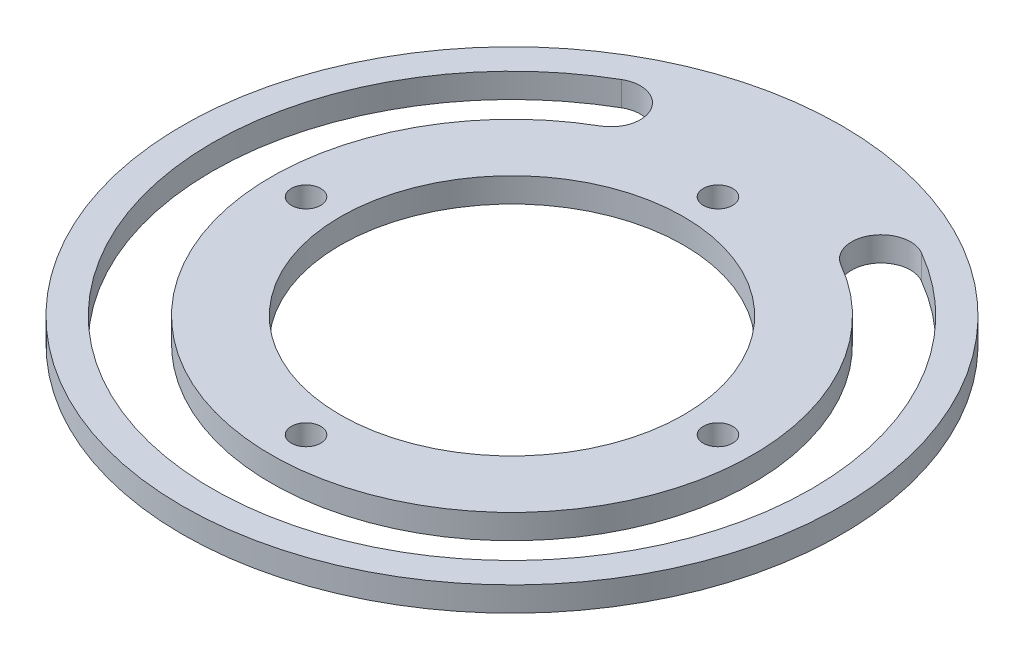
SolidWorks part; units mm, degrees
ref_plane "Front Plane" through (0, 0, 0) normal (0, 0, 1) x (1, 0, 0)
ref_plane "Top Plane" through (0, 0, 0) normal (0, 1, 0) x (1, 0, 0)
ref_plane "Right Plane" through (0, 0, 0) normal (1, 0, 0) x (0, 0, -1)
sketch "Sketch1" plane through (0, 0, 0) normal (0, 1, 0) x (1, 0, 0)
  line L0 (0, 0) -> (0, 26.67) construction
  circle A0 centre (0, 0) radius 22.225
  circle A1 centre (0, 0) radius 42.672
  circle A2 centre (0, 26.67) radius 1.905
  circle A7 centre (26.67, 0) radius 1.905
  circle A8 centre (0, -26.67) radius 1.905
  circle A9 centre (-26.67, 0) radius 1.905
  point P16 (0.3175, -0.3175)
  point P17 (0, 0)
  dimension "D1" = 44.45
  dimension "D3" = 3.81
  dimension "D2" = 85.344
  dimension "D4" = 26.67
  dimension "D5" = 4
extrude "Boss-Extrude1" add sketch "Sketch1" along normal blind 3.175
sketch "Sketch2" plane through (0, 3.175, 0) normal (0, 1, 0) x (1, 0, 0)
  line L0 (0, 0) -> (31.1785, 0) construction
  line L1 (0, 0) -> (0, 26.67) construction
  line L2 (0, 0) -> (0, 42.672) construction
  line L3 (0, 0) -> (-17.4943, 30.3009) construction
  line L4 (0, 0) -> (30.9704, 53.6423) construction
  line L5 (-65.0955, 30.3009) -> (17.4943, 30.3009) construction
  circle A1 centre (0, 0) radius 42.672 construction
  arc A2 (-15.5893, 27.0014) -> (-19.3993, 33.6005) centre (-17.4943, 30.3009) ccw
  arc A5 (19.3993, 33.6005) -> (15.5893, 27.0014) centre (17.4943, 30.3009) ccw
  arc A6 (-19.3993, 33.6005) -> (19.3993, 33.6005) centre (0, 0) ccw
  arc A8 (-15.5893, 27.0014) -> (15.5893, 27.0014) centre (0, 0) ccw
  point P17 (17.4943, 30.3009)
  dimension "D7" = 7.62
  dimension "D2" = 26.67
  dimension "D3" = 42.672
  dimension "D4" = 30
  dimension "D5" = 30
  dimension "D6" = 34.9885
extrude "Cut-Extrude1" cut sketch "Sketch2" against normal through all
